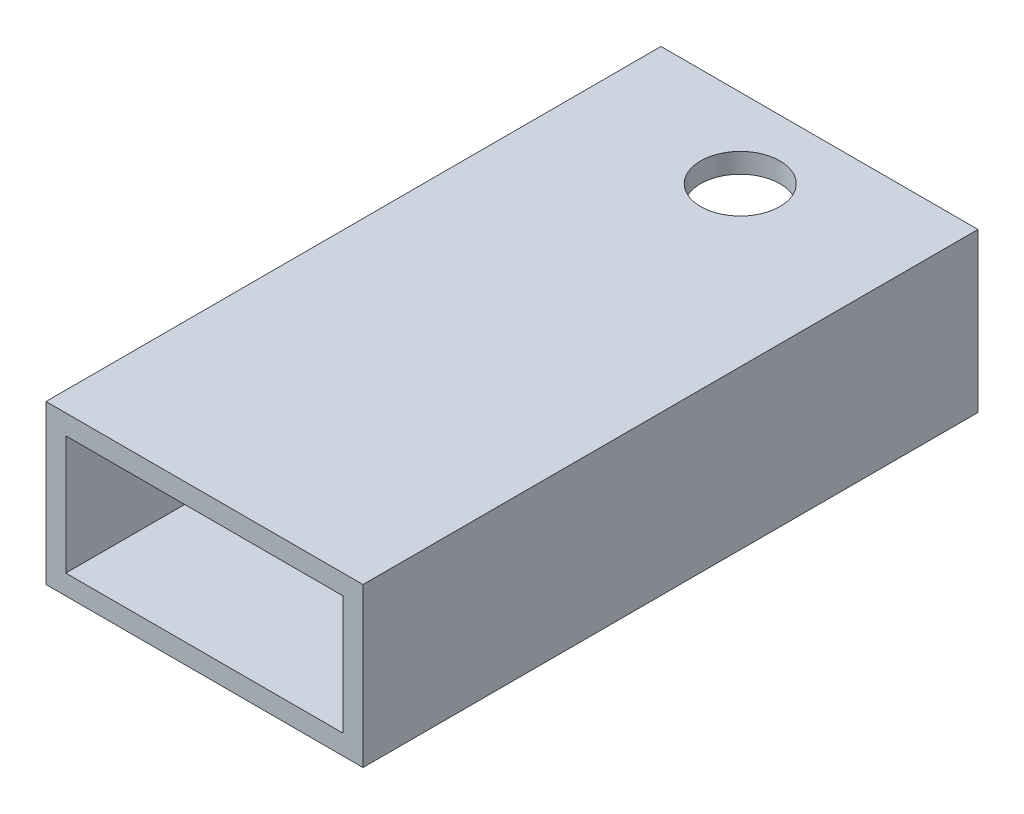
SolidWorks part; units mm, degrees
ref_plane "Front Plane" through (0, 0, 0) normal (0, 0, 1) x (1, 0, 0)
ref_plane "Top Plane" through (0, 0, 0) normal (0, 1, 0) x (1, 0, 0)
ref_plane "Right Plane" through (0, 0, 0) normal (1, 0, 0) x (0, 0, -1)
sketch "Sketch1" plane through (0, 0, 0) normal (0, 0, 1) x (1, 0, 0)
  line L0 (3.175, 3.175) -> (47.625, 3.175)
  line L1 (0, 0) -> (50.8, 0)
  line L2 (0, 0) -> (0, 25.4)
  line L3 (0, 25.4) -> (50.8, 25.4)
  line L4 (50.8, 0) -> (50.8, 25.4)
  line L5 (47.625, 3.175) -> (47.625, 22.225)
  line L6 (3.175, 22.225) -> (47.625, 22.225)
  line L7 (3.175, 3.175) -> (3.175, 22.225)
  dimension "D1" = 50.8
  dimension "D2" = 25.4
  dimension "D3" = 3.175
extrude "Boss-Extrude1" add sketch "Sketch1" along normal blind 98.552
sketch "Sketch2" plane through (0, 0, 0) normal (0, -1, 0) x (1, 0, 0)
  line L0 (0, 0) -> (50.8, 0) construction
  line L1 (50.8, 98.552) -> (50.8, 0) construction
  circle A0 centre (25.4, 12.7) radius 6.35
  point P2 (25.4, 0)
  dimension "D1" = 12.7
  dimension "D2" = 12.7
  dimension "D3" = 25.4
extrude "Cut-Extrude1" cut sketch "Sketch2" against normal through all
